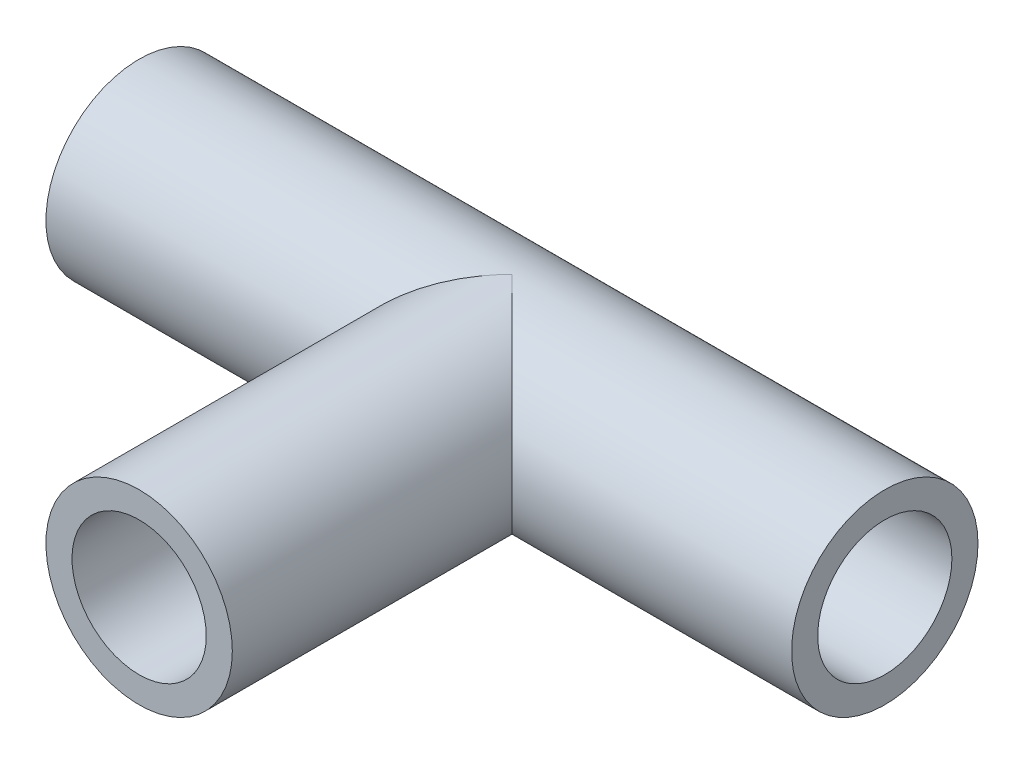
SolidWorks part; units mm, degrees
ref_plane "Front Plane" through (0, 0, 0) normal (0, 0, 1) x (1, 0, 0)
ref_plane "Top Plane" through (0, 0, 0) normal (0, 1, 0) x (1, 0, 0)
ref_plane "Right Plane" through (0, 0, 0) normal (1, 0, 0) x (0, 0, -1)
sketch "Sketch1" plane through (0, 0, 0) normal (1, 0, 0) x (0, 0, -1)
  circle A0 centre (0, 0) radius 4
sketch "Sketch14" plane through (0, 0, 0) normal (1, 0, 0) x (0, 0, -1)
  circle A0 centre (0, 0) radius 3.75
  dimension "D1" = 7.5
extrude "Boss-Extrude1" add sketch "Sketch14" along normal blind 30
sketch "Sketch15" plane through (30, 0, 0) normal (1, 0, 0) x (0, 0, -1)
  circle A0 centre (0, 0) radius 2.7
extrude "Cut-Extrude4" cut sketch "Sketch15" against normal blind 30
sketch "Sketch16" plane through (0, 0, 0) normal (0, 0, 1) x (1, 0, 0)
  line L0 (0, 0) -> (30, 0)
  line L1 (0, -4) -> (0, 4) construction
  line L2 (30, -3.75) -> (30, 3.75) construction
  circle A0 centre (15, 0) radius 3.75
  circle A1 centre (15, 0) radius 2.7
extrude "Boss-Extrude2" add sketch "Sketch16" along normal blind 15 contours A1 L0 A0 | A1 L0 A0 | L0 A1 | L0 A1
sketch "Sketch17" plane through (0, 0, 0) normal (1, 0, 0) x (0, 0, -1)
  circle A0 centre (0, 0) radius 2.7
extrude "Cut-Extrude5" cut sketch "Sketch17" along normal blind 25
sketch "Sketch18" plane through (0, 0, 0) normal (0, 0, 1) x (1, 0, 0)
  circle A0 centre (15, 0) radius 2.7
extrude "Cut-Extrude6" cut sketch "Sketch18" along normal blind 25
